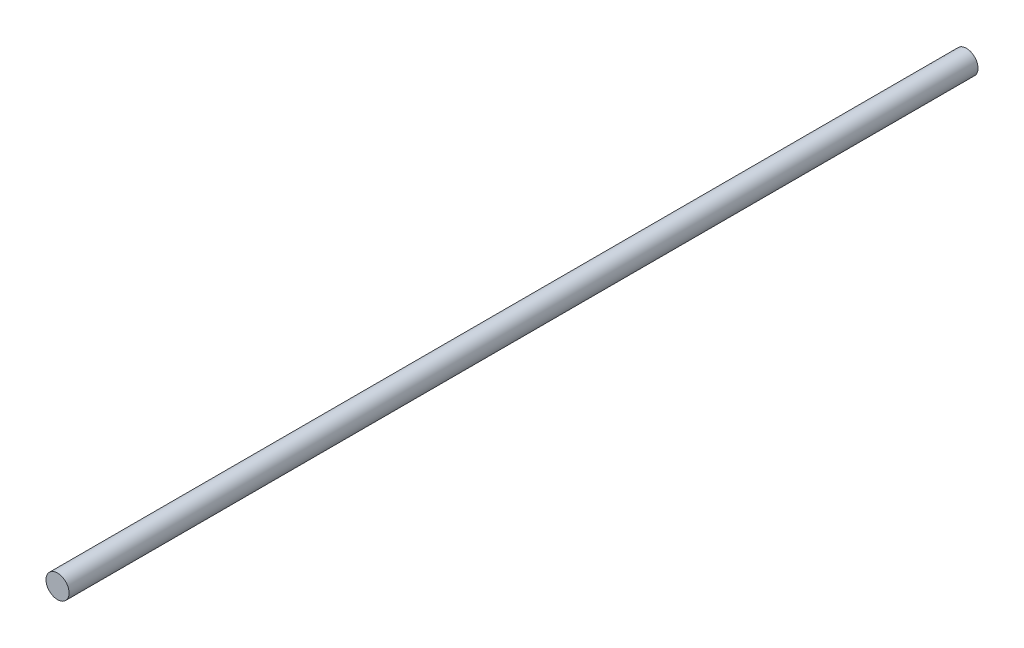
SolidWorks part; units mm, degrees
material "Plain Carbon Steel"
ref_plane "Front Plane" through (0, 0, 0) normal (0, 0, 1) x (1, 0, 0)
ref_plane "Top Plane" through (0, 0, 0) normal (0, 1, 0) x (1, 0, 0)
ref_plane "Right Plane" through (0, 0, 0) normal (1, 0, 0) x (0, 0, -1)
sketch "Sketch1" plane through (0, 0, 0) normal (0, 0, 1) x (1, 0, 0)
  circle A0 centre (0, 0) radius 4
  dimension "D1" = 8
extrude "Boss-Extrude1" add sketch "Sketch1" along normal mid plane 315
